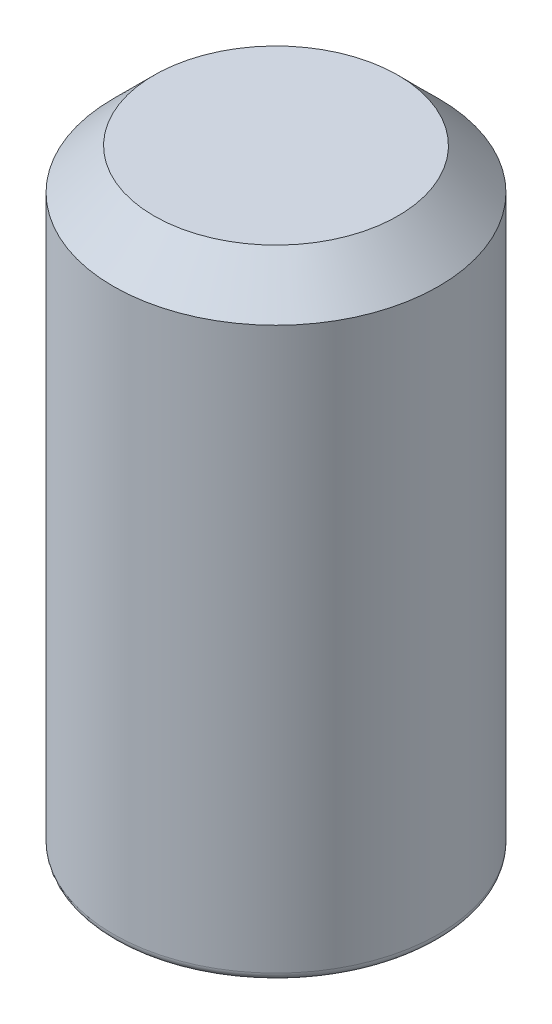
SolidWorks part; units mm, degrees
ref_plane "前视基准面" through (0, 0, 0) normal (0, 0, 1) x (1, 0, 0)
ref_plane "上视基准面" through (0, 0, 0) normal (0, 1, 0) x (1, 0, 0)
ref_plane "右视基准面" through (0, 0, 0) normal (1, 0, 0) x (0, 0, -1)
sketch "草图1" plane through (0, 0, 0) normal (0, 1, 0) x (1, 0, 0)
  circle A0 centre (0, 0) radius 4
  dimension "D1" = 8
extrude "凸台-拉伸1" add sketch "草图1" along normal blind 15
chamfer "倒角1" distance 1 angle 45 1 edges at (0, 15, 4)
fillet "圆角1" radius 0.2 1 edges at (0, 0, 4)
sketch "草图2" plane through (0, 0, 0) normal (1, 0, 0) x (0, 0, -1)
  line L0 (0, 0) -> (0, 15) construction
  line L1 (3, 15) -> (-3, 15) construction
sketch "草图3" plane through (0, 0, 0) normal (0, 0, 1) x (1, 0, 0)
  line L0 (4, 14) -> (4, 0.2) construction
